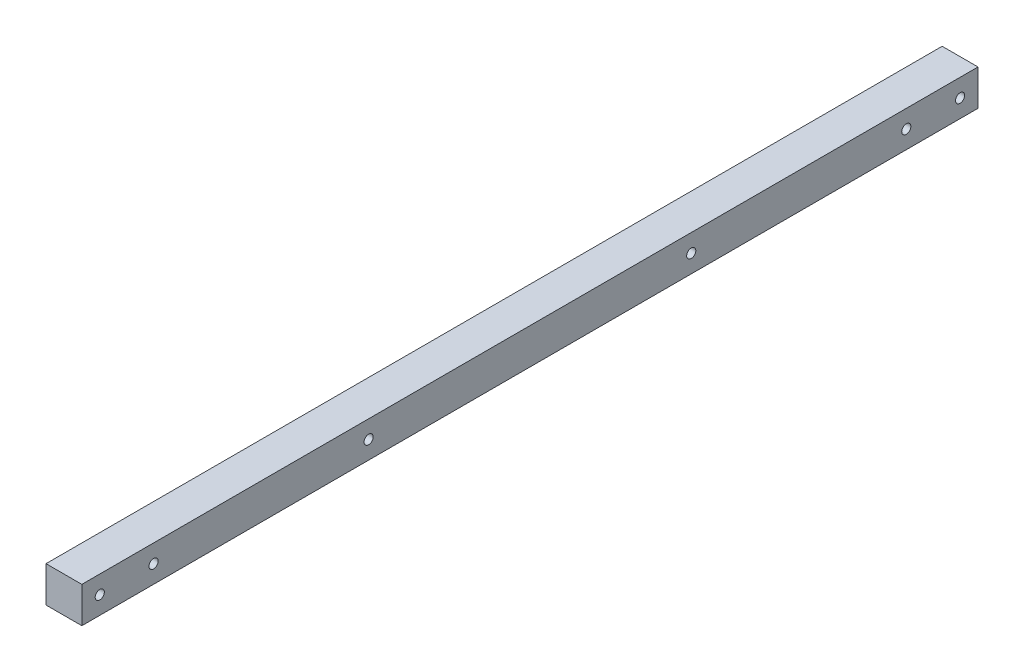
SolidWorks part; units mm, degrees
ref_plane "Front" through (0, 0, 0) normal (0, 0, 1) x (1, 0, 0)
ref_plane "Top" through (0, 0, 0) normal (0, 1, 0) x (1, 0, 0)
ref_plane "Right" through (0, 0, 0) normal (1, 0, 0) x (0, 0, -1)
sketch "草图1" plane through (0, 0, 0) normal (0, 0, 1) x (1, 0, 0)
  line L1 (-10, 10) -> (10, 10)
  line L2 (-10, 10) -> (-10, -10)
  line L3 (-10, -10) -> (10, -10)
  line L4 (10, 10) -> (10, -10)
  line L5 (-10, 10) -> (10, -10) construction
  line L6 (-10, -10) -> (10, 10) construction
  point P0 (0, 0)
  dimension "D1" = 20
  dimension "D2" = 20
extrude "凸台-拉伸2" add sketch "草图1" along normal blind 500
sketch "草图2" plane through (10, 0, 0) normal (1, 0, 0) x (0, 0, -1)
  line L0 (0, -10) -> (0, 10) construction
  circle A0 centre (-10, 0) radius 2.55
  circle A1 centre (-40, 0) radius 2.55
  dimension "D1" = 5.1
  dimension "D3" = 5.1
  dimension "D4" = 30
  dimension "D2" = 10
extrude "切除-拉伸1" cut sketch "草图2" against normal up to next
sketch "草图3" plane through (0, -10, 0) normal (0, -1, 0) x (1, 0, 0)
  line L0 (10, 500) -> (10, 0) construction
  line L1 (-10, 0) -> (10, 0)
  line L2 (-10, 0) -> (-10, 50)
  line L3 (-10, 50) -> (10, 50)
  line L4 (10, 0) -> (10, 50)
extrude "凸台-拉伸3" add sketch "草图3" along normal blind 20
sketch "草图4" plane through (10, 0, 0) normal (1, 0, 0) x (0, 0, -1)
  line L0 (-50, -30) -> (-50, -10) construction
  line L1 (0, -30) -> (0, 10) construction
  circle A0 centre (-40, -20) radius 2.55
  circle A1 centre (-10, -20) radius 2.55
  dimension "D1" = 5.1
  dimension "D2" = 5.1
  dimension "D3" = 10
  dimension "D4" = 10
extrude "切除-拉伸2" cut sketch "草图4" against normal blind 20
sketch "草图5" plane through (0, 0, 500) normal (0, 0, 1) x (1, 0, 0)
  line L1 (-10, -10) -> (10, -10)
  line L2 (-10, -10) -> (-10, 10)
  line L3 (-10, 10) -> (10, 10)
  line L4 (10, -10) -> (10, 10)
extrude "切除-拉伸3" cut sketch "草图5" against normal blind 250
mirror "镜向2" about plane through (0, 0, 250) normal (0, 0, -1) of "凸台-拉伸3", "凸台-拉伸2"
sketch "草图6" plane through (10, 0, 0) normal (1, 0, 0) x (0, 0, -1)
  line L0 (-500, -30) -> (-500, 10) construction
  circle A0 centre (-490, 0) radius 2.55
  circle A1 centre (-460, 0) radius 2.55
  circle A2 centre (-460, -20) radius 2.55
  circle A3 centre (-490, -20) radius 2.55
  circle A4 centre (-10, 0) radius 2.55
  circle A5 centre (-40, 0) radius 2.55
  dimension "D1" = 5.1
  dimension "D2" = 5.1
  dimension "D3" = 5.1
  dimension "D4" = 5.1
  dimension "D9" = 5.1
  dimension "D10" = 5.1
  dimension "D5" = 10
  dimension "D6" = 30
  dimension "D7" = 10
  dimension "D8" = 30
extrude "切除-拉伸4" cut sketch "草图6" against normal up to next
sketch "草图7" plane through (10, 0, 0) normal (1, 0, 0) x (0, 0, -1)
  line L1 (-450, -10) -> (-500, -10)
  line L2 (-450, -10) -> (-450, -30)
  line L3 (-450, -30) -> (-500, -30)
  line L4 (-500, -10) -> (-500, -30)
  line L5 (-50, -10) -> (0, -10)
  line L6 (-50, -10) -> (-50, -30)
  line L7 (-50, -30) -> (0, -30)
  line L8 (0, -10) -> (0, -30)
extrude "切除-拉伸5" cut sketch "草图7" against normal blind 250
sketch "草图8" plane through (10, 0, 0) normal (1, 0, 0) x (0, 0, -1)
  circle A0 centre (-340, 0) radius 2.55
  circle A1 centre (-160, 0) radius 2.55
  circle A2 centre (-490, 0) radius 2.55 construction
  circle A3 centre (-10, 0) radius 2.55 construction
  dimension "D1" = 5.1
  dimension "D2" = 5.1
  dimension "D3" = 150
  dimension "D4" = 150
extrude "切除-拉伸6" cut sketch "草图8" against normal up to next
